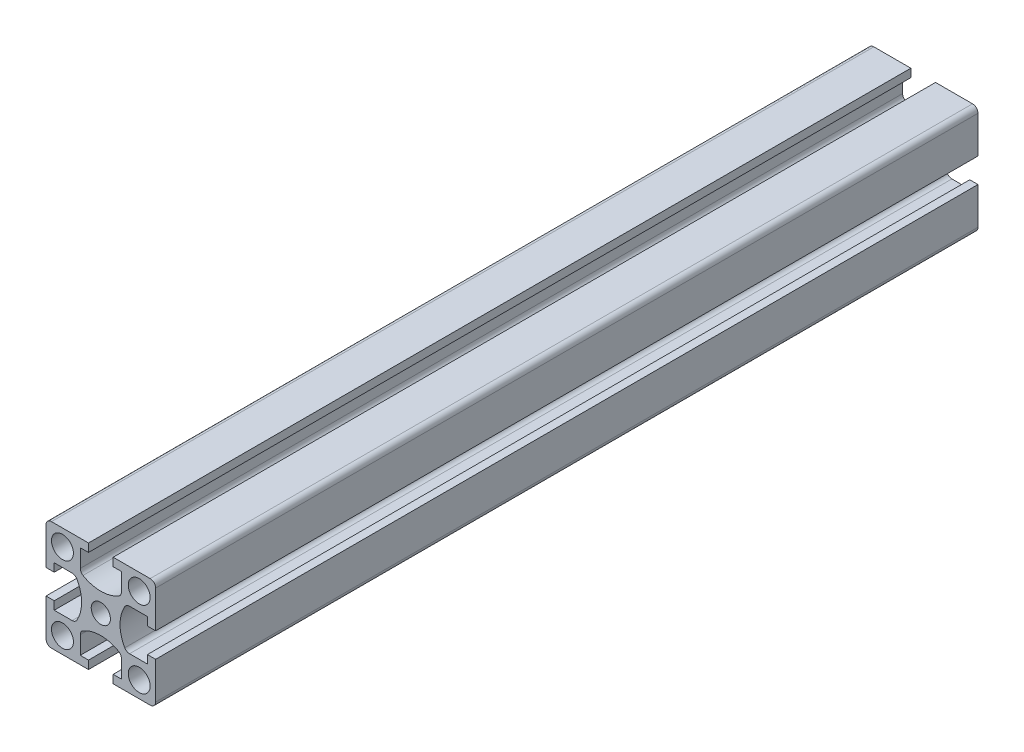
SolidWorks part; units mm, degrees
ref_plane "Front Plane" through (0, 0, 0) normal (0, 0, 1) x (1, 0, 0)
ref_plane "Top Plane" through (0, 0, 0) normal (0, 1, 0) x (1, 0, 0)
ref_plane "Right Plane" through (0, 0, 0) normal (1, 0, 0) x (0, 0, -1)
sketch "Sketch1" plane through (0, 0, 0) normal (0, 0, 1) x (1, 0, 0)
  line L64 (-10, 9) -> (-10, 2.25)
  line L65 (-10, 2.25) -> (-8.5, 2.25)
  line L66 (-8.5, 2.25) -> (-8.5, 3.75)
  line L67 (-8.5, 3.75) -> (-5.2369, 3.75)
  line L68 (-5.2369, -3.75) -> (-8.5, -3.75)
  line L69 (-8.5, -3.75) -> (-8.5, -2.25)
  line L70 (-8.5, -2.25) -> (-10, -2.25)
  line L71 (-10, -2.25) -> (-10, -9)
  line L72 (-9, -10) -> (-2.25, -10)
  line L73 (-2.25, -10) -> (-2.25, -8.5)
  line L74 (-2.25, -8.5) -> (-3.75, -8.5)
  line L75 (-3.75, -8.5) -> (-3.75, -5.2369)
  line L76 (3.75, -5.2369) -> (3.75, -8.5)
  line L77 (3.75, -8.5) -> (2.25, -8.5)
  line L78 (2.25, -8.5) -> (2.25, -10)
  line L79 (2.25, -10) -> (9, -10)
  line L80 (10, -9) -> (10, -2.25)
  line L81 (10, -2.25) -> (8.5, -2.25)
  line L82 (8.5, -2.25) -> (8.5, -3.75)
  line L83 (8.5, -3.75) -> (5.2369, -3.75)
  line L84 (5.2369, 3.75) -> (8.5, 3.75)
  line L85 (8.5, 3.75) -> (8.5, 2.25)
  line L86 (8.5, 2.25) -> (10, 2.25)
  line L87 (10, 2.25) -> (10, 9)
  line L88 (9, 10) -> (2.25, 10)
  line L89 (2.25, 10) -> (2.25, 8.5)
  line L90 (2.25, 8.5) -> (3.75, 8.5)
  line L91 (3.75, 8.5) -> (3.75, 5.2369)
  line L92 (-3.75, 5.2369) -> (-3.75, 8.5)
  line L93 (-3.75, 8.5) -> (-2.25, 8.5)
  line L94 (-2.25, 8.5) -> (-2.25, 10)
  line L95 (-2.25, 10) -> (-9, 10)
  circle A5 centre (-7, -7) radius 2
  circle A6 centre (7, -7) radius 2
  circle A7 centre (7, 7) radius 2
  circle A8 centre (0, 0) radius 1.75
  circle A9 centre (-7, 7) radius 2
  arc A32 (-9, 10) -> (-10, 9) centre (-9, 9) ccw
  arc A33 (-4.3708, 3.25) -> (-5.2369, 3.75) centre (-5.2369, 2.75) ccw
  arc A34 (-4.3708, -3.25) -> (-4.3708, 3.25) centre (-10, 0) ccw
  arc A35 (-5.2369, -3.75) -> (-4.3708, -3.25) centre (-5.2369, -2.75) ccw
  arc A36 (-10, -9) -> (-9, -10) centre (-9, -9) ccw
  arc A37 (-3.25, -4.3708) -> (-3.75, -5.2369) centre (-2.75, -5.2369) ccw
  arc A38 (3.25, -4.3708) -> (-3.25, -4.3708) centre (0, -10) ccw
  arc A39 (3.75, -5.2369) -> (3.25, -4.3708) centre (2.75, -5.2369) ccw
  arc A40 (9, -10) -> (10, -9) centre (9, -9) ccw
  arc A41 (4.3708, -3.25) -> (5.2369, -3.75) centre (5.2369, -2.75) ccw
  arc A42 (4.3708, 3.25) -> (4.3708, -3.25) centre (10, 0) ccw
  arc A43 (5.2369, 3.75) -> (4.3708, 3.25) centre (5.2369, 2.75) ccw
  arc A44 (10, 9) -> (9, 10) centre (9, 9) ccw
  arc A45 (3.25, 4.3708) -> (3.75, 5.2369) centre (2.75, 5.2369) ccw
  arc A46 (-3.25, 4.3708) -> (3.25, 4.3708) centre (0, 10) ccw
  arc A47 (-3.75, 5.2369) -> (-3.25, 4.3708) centre (-2.75, 5.2369) ccw
extrude "Boss-Extrude1" add sketch "Sketch1" along normal blind 150
